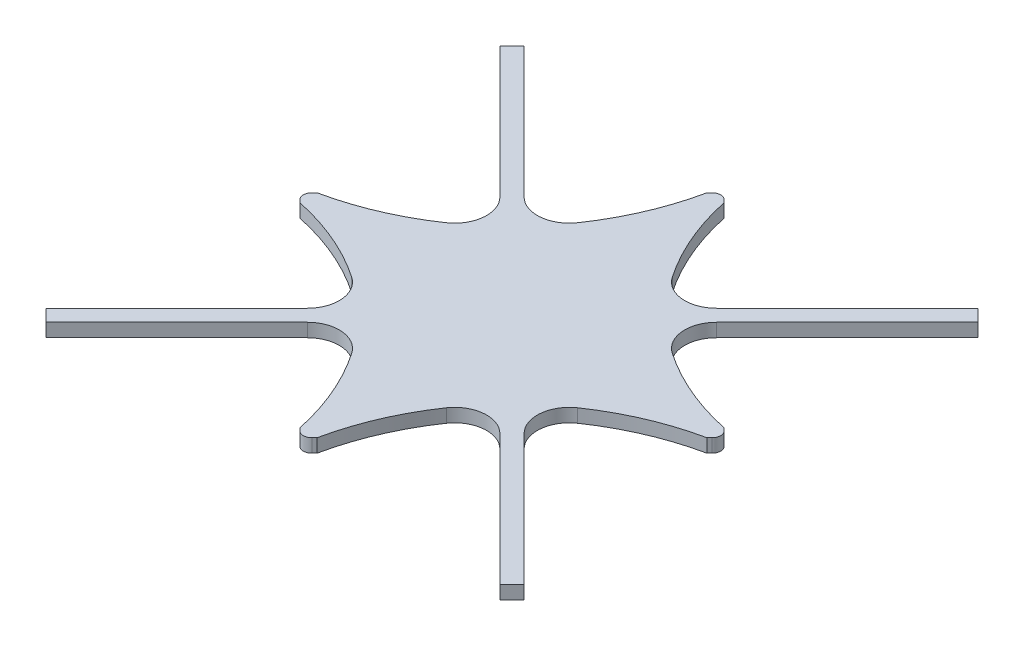
SolidWorks part; units mm, degrees
ref_plane "Front Plane" through (0, 0, 0) normal (0, 0, 1) x (1, 0, 0)
ref_plane "Top Plane" through (0, 0, 0) normal (0, 1, 0) x (1, 0, 0)
ref_plane "Right Plane" through (0, 0, 0) normal (1, 0, 0) x (0, 0, -1)
sketch "Framesketch" plane through (0, 0, 0) normal (0, 1, 0) x (1, 0, 0)
  line L0 (0, 0) -> (-30.445, -30.445) construction
  line L1 (-27.0401, 28.4826) -> (-8.4756, 9.9181)
  line L2 (0, 0) -> (-30.445, 30.445) construction
  line L3 (0, 0) -> (0, 25.275) construction
  line L4 (0, 0) -> (25.275, 0) construction
  line L5 (0, 0) -> (0, -25.275) construction
  line L6 (0, 0) -> (-25.275, 0) construction
  line L7 (0, 25.275) -> (-1.023, 24.252)
  line L8 (-25.275, 0) -> (-24.252, -1.023)
  line L9 (0, -25.275) -> (1.023, -24.252)
  line L10 (-19.06, -19.06) -> (-19.5515, -19.06)
  line L11 (25.275, 0) -> (24.252, 1.023)
  line L12 (-19.06, 19.5515) -> (-19.5515, 19.5515)
  line L13 (-24.252, 1.023) -> (-25.275, 0)
  line L14 (-28.4826, 27.0401) -> (-9.9181, 8.4756)
  line L15 (27.0401, 28.4826) -> (28.4826, 27.0401)
  line L16 (28.4826, 27.0401) -> (9.9181, 8.4756)
  line L17 (27.0401, 28.4826) -> (8.4756, 9.9181)
  line L18 (28.4826, -27.0401) -> (27.0401, -28.4826)
  line L19 (27.0401, -28.4826) -> (8.4756, -9.9181)
  line L20 (28.4826, -27.0401) -> (9.9181, -8.4756)
  line L21 (1.023, 24.252) -> (0, 25.275)
  line L22 (24.252, -1.023) -> (25.275, 0)
  line L23 (-1.023, -24.252) -> (0, -25.275)
  line L24 (-28.4826, 27.0401) -> (-27.0401, 28.4826)
  line L25 (28.7527, -27.3102) -> (9.9181, -8.4756) [skipped]
  line L26 (27.3102, -28.7527) -> (8.4756, -9.9181) [skipped]
  line L27 (-27.3102, -28.7527) -> (-8.4756, -9.9181) [skipped]
  line L28 (-28.7527, -27.3102) -> (-9.9181, -8.4756) [skipped]
  line L29 (27.3102, 28.7527) -> (8.4756, 9.9181) [skipped]
  line L30 (28.7527, 27.3102) -> (9.9181, 8.4756) [skipped]
  line L31 (-27.0401, -28.4826) -> (-28.4826, -27.0401)
  line L32 (-28.4826, -27.0401) -> (-9.9181, -8.4756)
  line L33 (-27.0401, -28.4826) -> (-8.4756, -9.9181)
  arc A2 (-8.4756, 9.9181) -> (-1.023, 24.252) centre (-30.445, 30.445) ccw
  arc A4 (-24.252, 1.023) -> (-9.9181, 8.4756) centre (-30.445, 30.445) ccw
  arc A7 (9.9181, 8.4756) -> (24.252, 1.023) centre (30.445, 30.445) ccw
  arc A8 (1.023, 24.252) -> (8.4756, 9.9181) centre (30.445, 30.445) ccw
  arc A10 (8.4756, -9.9181) -> (1.023, -24.252) centre (30.445, -30.445) ccw
  arc A11 (24.252, -1.023) -> (9.9181, -8.4756) centre (30.445, -30.445) ccw
  arc A13 (-9.9181, -8.4756) -> (-24.252, -1.023) centre (-30.445, -30.445) ccw
  arc A14 (-1.023, -24.252) -> (-8.4756, -9.9181) centre (-30.445, -30.445) ccw
  point P26 (0, 0)
  point P51 (0, 0)
  point P64 (0, 0)
  dimension "D1" = 4
  dimension "D2" = 1.02
  dimension "D3" = 4
  dimension "D4" = 4
extrude "Boss-Extrude1" add sketch "Framesketch" along normal blind 1.6
fillet "Fillet1" radius 1.016 4 edges at (25.275, 0.8, 0) (0, 0.8, 25.275) (-25.275, 0.8, 0) (0, 0.8, -25.275)
fillet "Fillet3" radius 3.81 8 edges at (8.4756, 0.8, 9.9181) (9.9181, 0.8, 8.4756) (8.4756, 0.8, -9.9181) (9.9181, 0.8, -8.4756) (-8.4756, 0.8, -9.9181) (-9.9181, 0.8, -8.4756) (-9.9181, 0.8, 8.4756) (-8.4756, 0.8, 9.9181)
